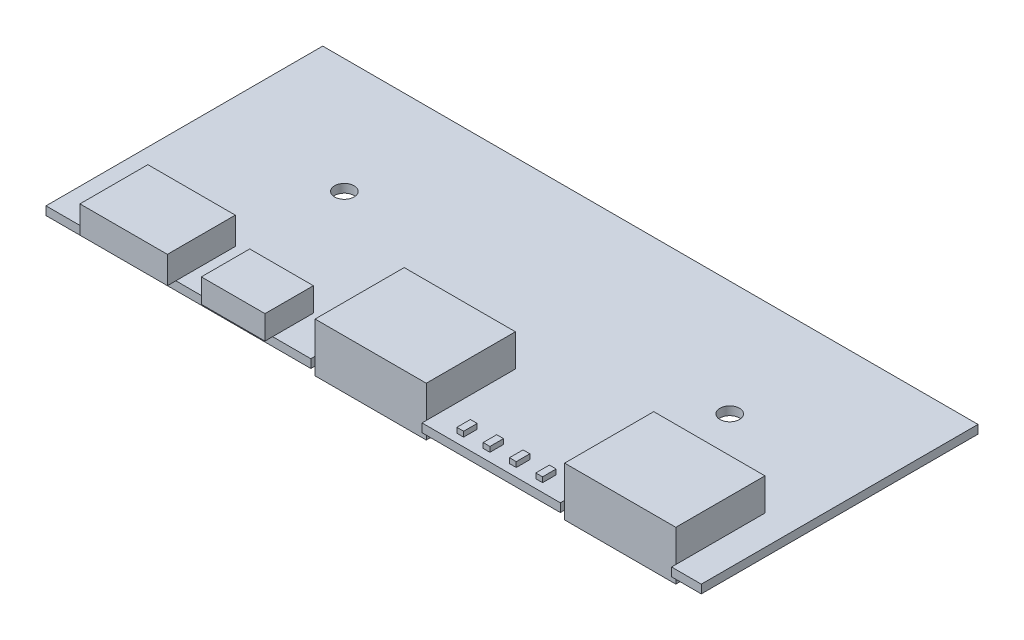
SolidWorks part; units mm, degrees
ref_plane "Front Plane" through (0, 0, 0) normal (0, 0, 1) x (1, 0, 0)
ref_plane "Top Plane" through (0, 0, 0) normal (0, 1, 0) x (1, 0, 0)
ref_plane "Right Plane" through (0, 0, 0) normal (1, 0, 0) x (0, 0, -1)
sketch "Sketch1" plane through (0, 0, 0) normal (0, 1, 0) x (1, 0, 0)
  line L1 (38.6, -16.3) -> (-38.6, -16.3)
  line L2 (38.6, -16.3) -> (38.6, 16.3)
  line L3 (38.6, 16.3) -> (-38.6, 16.3)
  line L4 (-38.6, -16.3) -> (-38.6, 16.3)
  line L5 (38.6, -16.3) -> (-38.6, 16.3) construction
  line L6 (38.6, 16.3) -> (-38.6, -16.3) construction
  point P0 (0, 0)
  dimension "D1" = 77.2
  dimension "D2" = 32.6
extrude "Boss-Extrude1" add sketch "Sketch1" along normal blind 1
sketch "Sketch2" plane through (0, 1, 0) normal (0, 1, 0) x (1, 0, 0)
  line L0 (-38.6, -16.3) -> (38.6, -16.3) construction
  line L1 (35.1, -16.3) -> (22, -16.3)
  line L2 (35.1, -16.3) -> (35.1, -5.3)
  line L3 (35.1, -5.3) -> (22, -5.3)
  line L4 (22, -16.3) -> (22, -5.3)
  line L5 (38.6, -16.3) -> (38.6, 16.3) construction
  line L7 (5.7, -16.3) -> (-7.4, -16.3)
  line L8 (5.7, -16.3) -> (5.7, -5.3)
  line L9 (5.7, -5.3) -> (-7.4, -5.3)
  line L10 (-7.4, -16.3) -> (-7.4, -5.3)
  dimension "D1" = 13.1
  dimension "D2" = 11
  dimension "D3" = 3.5
  dimension "D4" = 42.5
extrude "Boss-Extrude2" add sketch "Sketch2" along normal blind 3.8 and the other way blind 2
sketch "Sketch3" plane through (0, 1, 0) normal (0, 1, 0) x (1, 0, 0)
  line L0 (-38.6, -16.3) -> (-7.4, -16.3) construction
  line L1 (-19.4, -11.5) -> (-11.9, -11.5)
  line L2 (-19.4, -11.5) -> (-19.4, -17.2)
  line L3 (-19.4, -17.2) -> (-11.9, -17.2)
  line L4 (-11.9, -11.5) -> (-11.9, -17.2)
  line L5 (5.7, -16.3) -> (5.7, -5.3) construction
  dimension "D1" = 7.5
  dimension "D2" = 5.7
  dimension "D3" = 0.9
  dimension "D4" = 25.1
extrude "Boss-Extrude3" add sketch "Sketch3" along normal blind 2.8
sketch "Sketch4" plane through (0, 1, 0) normal (0, 1, 0) x (1, 0, 0)
  line L0 (-38.6, -16.3) -> (-19.4, -16.3) construction
  line L1 (-23.3, -9.3) -> (-33.6, -9.3)
  line L2 (-23.3, -9.3) -> (-23.3, -17.3)
  line L3 (-23.3, -17.3) -> (-33.6, -17.3)
  line L4 (-33.6, -9.3) -> (-33.6, -17.3)
  line L5 (-38.6, 16.3) -> (-38.6, -16.3) construction
  dimension "D1" = 10.3
  dimension "D2" = 8
  dimension "D3" = 1
  dimension "D4" = 5
extrude "Boss-Extrude4" add sketch "Sketch4" along normal blind 3.2
sketch "Sketch5" plane through (0, 0, 16.3) normal (0, 0, 1) x (1, 0, 0)
  line L1 (-7.4, 4.8) -> (5.7, 4.8)
  line L2 (-7.4, 4.8) -> (-7.4, -1)
  line L3 (-7.4, -1) -> (5.7, -1)
  line L4 (5.7, 4.8) -> (5.7, -1)
  line L5 (22, 4.8) -> (35.1, 4.8)
  line L6 (22, 4.8) -> (22, -1)
  line L7 (22, -1) -> (35.1, -1)
  line L8 (35.1, 4.8) -> (35.1, -1)
extrude "Cut-Extrude1" cut sketch "Sketch5" against normal blind 0.5
sketch "Sketch6" plane through (0, 1, 0) normal (0, 1, 0) x (1, 0, 0)
  line L0 (5.7, -16.3) -> (22, -16.3) construction
  line L1 (18.1, -13.7) -> (18.9, -13.7)
  line L2 (18.1, -13.7) -> (18.1, -15.3)
  line L3 (18.1, -15.3) -> (18.9, -15.3)
  line L4 (18.9, -13.7) -> (18.9, -15.3)
  line L5 (38.6, -16.3) -> (38.6, 16.3) construction
  dimension "D1" = 0.8
  dimension "D2" = 1.6
  dimension "D3" = 1
  dimension "D4" = 20.5
extrude "Boss-Extrude5" add sketch "Sketch6" along normal blind 0.6
pattern_linear "LPattern1" count 4 spacing 3.1 along (-1, 0, 0) of "Boss-Extrude5"
sketch "Sketch7" plane through (0, 0, 0) normal (0, -1, 0) x (1, 0, 0)
  line L0 (38.6, -16.3) -> (-38.6, -16.3) construction
  line L1 (-2.7, -0.3) -> (2.4, -0.3)
  line L2 (-2.7, -0.3) -> (-2.7, -5.4)
  line L3 (-2.7, -5.4) -> (2.4, -5.4)
  line L4 (2.4, -0.3) -> (2.4, -5.4)
  line L5 (-38.6, -16.3) -> (-38.6, 16.3) construction
  dimension "D1" = 5.1
  dimension "D2" = 16
  dimension "D3" = 41
extrude "Boss-Extrude6" add sketch "Sketch7" along normal blind 1.3
sketch "Sketch8" plane through (0, -1.3, 0) normal (0, -1, 0) x (1, 0, 0)
  line L0 (-0.15, -0.3) -> (-0.15, -5.4) construction
  line L1 (2.4, -0.3) -> (-2.7, -0.3) construction
  line L2 (-2.7, -5.4) -> (2.4, -5.4) construction
  circle A0 centre (-0.15, -2.85) radius 1
  dimension "D1" = 2
extrude "Boss-Extrude7" add sketch "Sketch8" along normal offset from surface (1.2 mm away) 2.5 up to face at (10.3875, 0, 9.35) offset beyond the face yes
fillet "Fillet1" radius 1 4 edges at (-2.7, -0.65, -0.3) (2.4, -0.65, -5.4) (-2.7, -0.65, -5.4) (2.4, -0.65, -0.3)
fillet "Fillet2" radius 0.5 8 edges at (2.1071, -1.3, -0.5929) (2.4, -1.3, -2.85) (2.1071, -1.3, -5.1071) (-0.15, -1.3, -5.4) (-2.4071, -1.3, -5.1071) (-2.7, -1.3, -2.85) (-2.4071, -1.3, -0.5929) (-0.15, -1.3, -0.3)
fillet "Fillet3" radius 0.1 1 edges at (-0.15, -2.5, -1.85)
sketch "Sketch9" plane through (0, 1, 0) normal (0, 1, 0) x (1, 0, 0)
  line L0 (-22.5, 2.75) -> (22.9, 2.75) construction
  line L1 (38.6, 16.3) -> (-38.6, 16.3) construction
  line L2 (38.6, -16.3) -> (38.6, 16.3) construction
  circle A0 centre (-22.5, 2.75) radius 1.15
  circle A1 centre (22.9, 2.75) radius 1.15
  dimension "D1" = 2.3
  dimension "D2" = 45.4
  dimension "D3" = 13.55
  dimension "D4" = 15.7
extrude "Cut-Extrude2" cut sketch "Sketch9" against normal through all
equation "\"D3@Sketch9\"=12.4+(2.3/2)"
